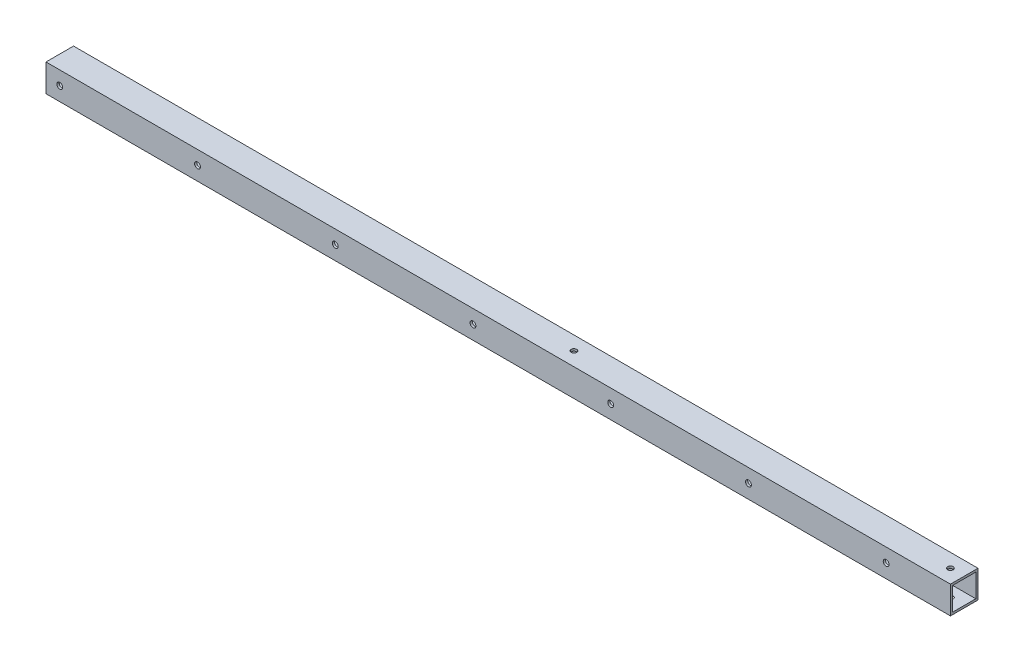
SolidWorks part; units mm, degrees
ref_plane "正面" through (0, 0, 0) normal (0, 0, 1) x (1, 0, 0)
ref_plane "平面" through (0, 0, 0) normal (0, 1, 0) x (1, 0, 0)
ref_plane "右側面" through (0, 0, 0) normal (1, 0, 0) x (0, 0, -1)
sketch "ｽｹｯﾁ2" plane through (0, 0, 0) normal (0, 0, 1) x (1, 0, 0)
  line L0 (0, 7.5) -> (7.5, 7.5) construction
  line L1 (0, 0) -> (492.5, 0)
  line L2 (0, 0) -> (0, 15)
  line L3 (0, 15) -> (492.5, 15)
  line L4 (492.5, 0) -> (492.5, 15)
  line L5 (7.5, 7.5) -> (9.1, 7.5) construction
  line L6 (232.5, 7.5) -> (307.5, 7.5) construction
  line L8 (457.5, 7.5) -> (492.5, 7.5) construction
  line L9 (232.5, 7.5) -> (157.5, 7.5) construction
  line L10 (157.5, 7.5) -> (82.5, 7.5) construction
  line L11 (82.5, 7.5) -> (7.5, 7.5) construction
  line L13 (307.5, 7.5) -> (382.5, 7.5) construction
  line L14 (382.5, 7.5) -> (457.5, 7.5) construction
  circle A0 centre (7.5, 7.5) radius 1.6
  circle A1 centre (457.5, 7.5) radius 1.6
  circle A2 centre (232.5, 7.5) radius 1.6
  circle A4 centre (82.5, 7.5) radius 1.6
  circle A5 centre (157.5, 7.5) radius 1.6
  circle A6 centre (307.5, 7.5) radius 1.6
  circle A7 centre (382.5, 7.5) radius 1.6
  point P21 (430.9839, 7.5)
  point P23 (493.3516, 7.5)
  dimension "D3" = 3.2
  dimension "D4" = 7.5
  dimension "D6" = 75
  dimension "D2" = 450
  dimension "D5" = 35
  dimension "D1" = 15
extrude "ﾎﾞｽ - 押し出し1" add sketch "ｽｹｯﾁ2" along normal blind 15
sketch "ｽｹｯﾁ3" plane through (492.5, 0, 0) normal (1, 0, 0) x (0, 0, -1)
  line L8 (-1.2, 1.2) -> (-1.2, 13.8)
  line L9 (-1.2, 13.8) -> (-13.8, 13.8)
  line L10 (-13.8, 13.8) -> (-13.8, 1.2)
  line L11 (-13.8, 1.2) -> (-1.2, 1.2)
  line L12 (-1.2, 1.2) -> (-1.2, 13.8)
  line L13 (-1.2, 13.8) -> (-13.8, 13.8)
  line L14 (-13.8, 13.8) -> (-13.8, 1.2)
  line L15 (-13.8, 1.2) -> (-1.2, 1.2)
  dimension "D1" = 1.2
extrude "ｶｯﾄ - 押し出し1" cut sketch "ｽｹｯﾁ3" against normal through all
sketch "ｽｹｯﾁ4" plane through (0, 15, 0) normal (0, 1, 0) x (1, 0, 0)
  line L0 (382.5, 0) -> (382.5, -15) construction
  line L1 (234.1, -15) -> (305.9, -15) construction
  line L3 (485, -7.5) -> (280, -7.5) construction
  line L4 (380.9, -13.8) -> (382.5, -13.8) construction
  line L5 (0, -13.8) -> (492.5, -13.8) construction
  line L6 (492.5, 0) -> (0, 0) construction
  line L7 (492.5, -15) -> (0, -15) construction
  line L8 (382.5, -13.8) -> (384.1, -13.8) construction
  line L9 (492.5, -15) -> (492.5, 0) construction
  circle A0 centre (280, -7.5) radius 1.5
  circle A1 centre (485, -7.5) radius 1.5
  point P9 (382.5, -7.5)
  dimension "D2" = 3
  dimension "D3" = 7.5
  dimension "D1" = 205
extrude "ｶｯﾄ - 押し出し2" cut sketch "ｽｹｯﾁ4" against normal through all
chamfer "面取り1" distance 1 angle 45 2 edges at (483.5, 0, 7.5) (278.5, 0, 7.5)
